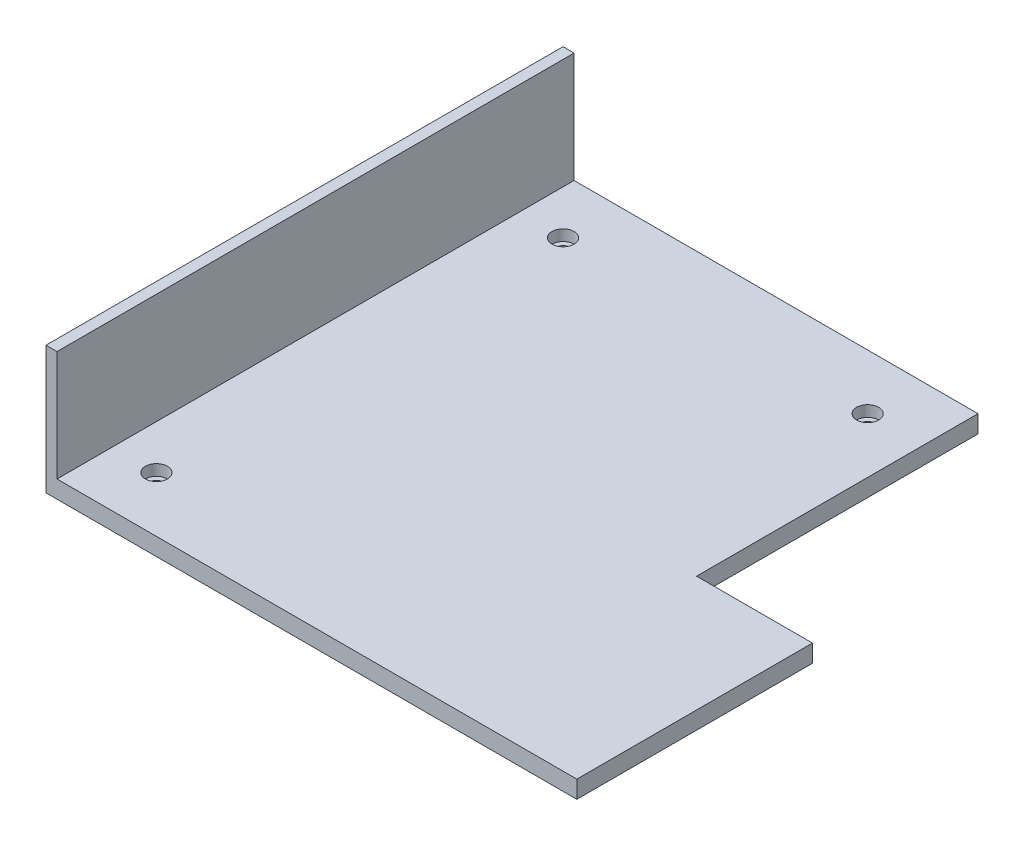
SolidWorks part; units mm, degrees
ref_plane "Front Plane" through (0, 0, 0) normal (0, 0, 1) x (1, 0, 0)
ref_plane "Top Plane" through (0, 0, 0) normal (0, 1, 0) x (1, 0, 0)
ref_plane "Right Plane" through (0, 0, 0) normal (1, 0, 0) x (0, 0, -1)
sketch "Sketch1" plane through (0, 0, 0) normal (0, 1, 0) x (1, 0, 0)
  line L1 (-96.2, 93.7) -> (96.2, 93.7)
  line L2 (-96.2, 93.7) -> (-96.2, -93.7)
  line L3 (-96.2, -93.7) -> (96.2, -93.7)
  line L4 (96.2, 93.7) -> (96.2, -93.7)
  line L5 (-96.2, 93.7) -> (96.2, -93.7) construction
  line L6 (-96.2, -93.7) -> (96.2, 93.7) construction
  point P0 (0, 0)
  dimension "D1" = 187.4
  dimension "D2" = 192.4
extrude "Boss-Extrude1" add sketch "Sketch1" along normal blind 6.35
sketch "Sketch2" plane through (0, 6.35, 0) normal (0, 1, 0) x (1, 0, 0)
  line L2 (-92.2, 89.7) -> (-92.2, -89.7)
  line L4 (96.2, -93.7) -> (96.2, 93.7)
  line L5 (96.2, 93.7) -> (-96.2, 93.7)
  line L6 (-96.2, 93.7) -> (-96.2, -93.7)
  line L7 (-96.2, -93.7) -> (96.2, -93.7)
  line L10 (-96.2, 93.7) -> (-96.2, -93.7)
  line L12 (92.2, 89.7) -> (-92.2, 89.7) construction
  line L13 (96.2, 93.7) -> (-96.2, 93.7) construction
  line L14 (92.2, -89.7) -> (92.2, 89.7) construction
  line L15 (96.2, -93.7) -> (96.2, 93.7) construction
  line L16 (-92.2, 89.7) -> (-92.2, 93.7)
  line L17 (96.2, 93.7) -> (-96.2, 93.7) construction
  line L18 (-92.2, 93.7) -> (-96.2, 93.7)
  line L22 (-92.2, -89.7) -> (92.2, -89.7) construction
  line L23 (-96.2, -93.7) -> (96.2, -93.7) construction
  line L24 (-92.2, -89.7) -> (-92.2, -93.7)
  line L25 (-96.2, -93.7) -> (96.2, -93.7) construction
  line L26 (-92.2, -93.7) -> (-96.2, -93.7)
  dimension "D1" = 0
  dimension "D2" = 4
extrude "Boss-Extrude2" add sketch "Sketch2" along normal blind 40
sketch "Sketch4" plane through (0, 6.35, 0) normal (0, 1, 0) x (1, 0, 0)
  line L0 (-92.2, -93.7) -> (96.2, -93.7) construction
  line L1 (96.2, 93.7) -> (54.2, 93.7)
  line L2 (96.2, 93.7) -> (96.2, -8.3)
  line L3 (96.2, -8.3) -> (54.2, -8.3)
  line L4 (54.2, 93.7) -> (54.2, -8.3)
  line L5 (-96.2, 93.7) -> (-96.2, -93.7) construction
  dimension "D1" = 85.4
  dimension "D2" = 150.4
extrude "Cut-Extrude1" cut sketch "Sketch4" against normal up to next
sketch "Sketch5" plane through (0, 6.35, 0) normal (0, 1, 0) x (1, 0, 0)
  line L0 (-96.2, 93.7) -> (-96.2, -93.7) construction
  line L1 (54.2, 93.7) -> (-96.2, 93.7) construction
  line L2 (54.2, 93.7) -> (54.2, 53.7) construction
  line L3 (54.2, 53.7) -> (-96.2, 53.7) construction
  line L4 (-96.2, 93.7) -> (-96.2, 53.7) construction
  line L5 (-92.2, -93.7) -> (96.2, -93.7) construction
  line L6 (-96.2, 93.7) -> (-56.2, 93.7) construction
  line L7 (-96.2, 93.7) -> (-96.2, -93.7) construction
  line L8 (-96.2, -93.7) -> (-56.2, -93.7) construction
  line L9 (-56.2, 93.7) -> (-56.2, -93.7) construction
  line L10 (-76.2, -93.7) -> (-76.2, 93.7) construction
  line L11 (54.2, 73.7) -> (-96.2, 73.7) construction
  point P18 (-76.2, 73.7)
  point P20 (-76.2, -73.7)
  point P24 (34.2, 73.7)
  dimension "D1" = 40
  dimension "D2" = 40
  dimension "D3" = 20
  dimension "D4" = 20
hole_wizard "CBORE for M4 SHCS1" positions "Sketch5" profile "Sketch6" counterbore size "M4" standard "ANSI Metric" end condition up to next
sketch "Sketch6" plane through (34.2, 6.35, -73.7) normal (1, 0, 0) x (0, 0, 1)
  line L0 (0, 0) -> (0, 6.35)
  line L1 (0, 6.35) -> (2.25, 6.35)
  line L3 (2.25, 6.35) -> (2.25, 4)
  line L4 (2.25, 4) -> (4, 4)
  line L5 (4, 4) -> (4, 0)
  line L7 (4, 0) -> (0, 0)
  line L11 (0, -6.35) -> (0, 107.95) construction
  dimension "Thru Hole Dia." = 4.5
  dimension "Thru Hole Depth" = 6.35
  dimension "C'Bore Dia." = 8
  dimension "C'Bore Depth" = 4
equation "\"D2@Sketch1\"=384.8/2"
equation "\"D2@Sketch4\"=152.4-2"
equation "\"D1@Sketch4\"=87.4-2"
